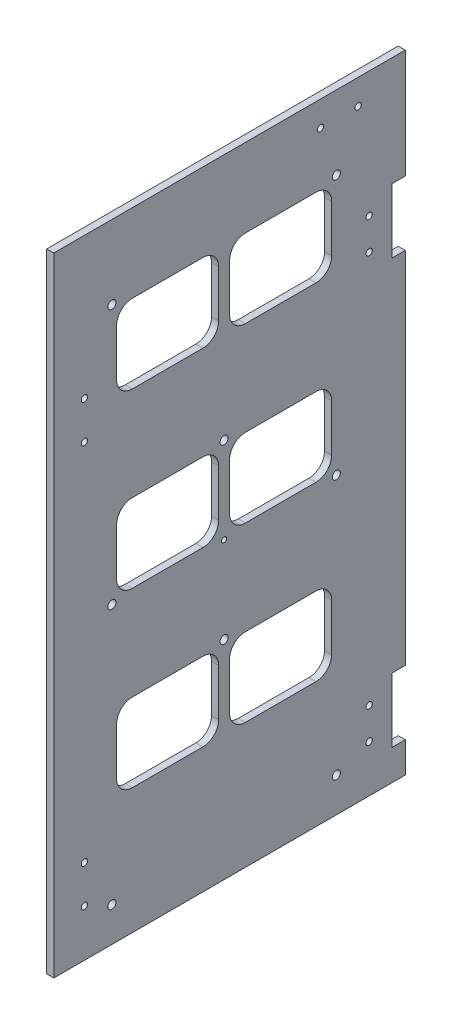
SolidWorks part; units mm, degrees
material "ABS PC"
ref_plane "前视基准面" through (0, 0, 0) normal (0, 0, 1) x (1, 0, 0)
ref_plane "上视基准面" through (0, 0, 0) normal (0, 1, 0) x (1, 0, 0)
ref_plane "右视基准面" through (0, 0, 0) normal (1, 0, 0) x (0, 0, -1)
sketch "草图1" plane through (0, 0, 0) normal (1, 0, 0) x (0, 0, -1)
  line L1 (0, 0) -> (-223.9, 0)
  line L2 (0, 0) -> (0, 400)
  line L3 (0, 400) -> (-223.9, 400)
  line L4 (-223.9, 0) -> (-223.9, 400)
  dimension "D1" = 223.9
  dimension "D2" = 400
extrude "凸台-拉伸1" add sketch "草图1" along normal blind 4.5
sketch "草图2" plane through (4.5, 0, 0) normal (1, 0, 0) x (0, 0, -1)
  line L0 (-204.4, 310) -> (-204.4, 286) construction
  line L1 (-204.4, 54) -> (-204.4, 30) construction
  line L2 (0, 400) -> (-223.9, 400) construction
  line L3 (-223.9, 400) -> (-223.9, 0) construction
  line L4 (-223.9, 0) -> (0, 0) construction
  line L5 (-54, 384) -> (-30, 384) construction
  line L6 (0, 0) -> (0, 400) construction
  line L7 (-23, 0) -> (-23, 306) construction
  line L9 (0, 330.5) -> (-8.5, 330.5)
  line L10 (0, 330.5) -> (0, 289.5)
  line L11 (0, 289.5) -> (-8.5, 289.5)
  line L12 (-8.5, 330.5) -> (-8.5, 289.5)
  line L13 (0, 19.5) -> (-8.5, 19.5)
  line L14 (0, 19.5) -> (0, 60.5)
  line L15 (0, 60.5) -> (-8.5, 60.5)
  line L16 (-8.5, 19.5) -> (-8.5, 60.5)
  circle A0 centre (-204.4, 310) radius 2
  circle A1 centre (-204.4, 286) radius 2
  circle A2 centre (-204.4, 54) radius 2
  circle A3 centre (-204.4, 30) radius 2
  circle A4 centre (-54, 384) radius 2
  circle A5 centre (-30, 384) radius 2
  circle A6 centre (-23, 320) radius 2
  circle A7 centre (-23, 300) radius 2
  circle A8 centre (-23, 50) radius 2
  circle A9 centre (-23, 30) radius 2
  dimension "D1" = 4
  dimension "D9" = 4
  dimension "D10" = 4
  dimension "D2" = 24
  dimension "D3" = 90
  dimension "D4" = 19.5
  dimension "D5" = 24
  dimension "D6" = 30
  dimension "D7" = 24
  dimension "D8" = 30
  dimension "D11" = 16
  dimension "D12" = 20
  dimension "D13" = 20
  dimension "D14" = 23
  dimension "D15" = 30
  dimension "D16" = 300
  dimension "D17" = 41
  dimension "D18" = 41
  dimension "D19" = 8.5
  dimension "D20" = 8.5
  dimension "D21" = 19.5
  dimension "D22" = 289.5
extrude "切除-拉伸1" cut sketch "草图2" against normal blind 10
sketch "草图3" plane through (4.5, 0, 0) normal (1, 0, 0) x (0, 0, -1)
  line L0 (-223.9, 400) -> (-223.9, 0) construction
  line L1 (-173.9, 130) -> (-128.9, 130)
  line L2 (-183.9, 120) -> (-183.9, 90)
  line L3 (-173.9, 80) -> (-128.9, 80)
  line L4 (-118.9, 120) -> (-118.9, 90)
  line L5 (-223.9, 0) -> (0, 0) construction
  line L34 (-101.9, 130) -> (-56.9, 130)
  line L35 (-111.9, 120) -> (-111.9, 90)
  line L36 (-101.9, 80) -> (-56.9, 80)
  line L37 (-46.9, 120) -> (-46.9, 90)
  line L38 (-101.9, 240) -> (-56.9, 240)
  line L39 (-111.9, 230) -> (-111.9, 200)
  line L40 (-101.9, 190) -> (-56.9, 190)
  line L41 (-46.9, 230) -> (-46.9, 200)
  line L42 (-101.9, 350) -> (-56.9, 350)
  line L43 (-111.9, 340) -> (-111.9, 310)
  line L44 (-101.9, 300) -> (-56.9, 300)
  line L45 (-46.9, 340) -> (-46.9, 310)
  line L46 (-173.9, 240) -> (-128.9, 240)
  line L47 (-183.9, 230) -> (-183.9, 200)
  line L48 (-173.9, 190) -> (-128.9, 190)
  line L49 (-118.9, 230) -> (-118.9, 200)
  line L50 (-173.9, 350) -> (-128.9, 350)
  line L51 (-183.9, 340) -> (-183.9, 310)
  line L52 (-173.9, 300) -> (-128.9, 300)
  line L53 (-118.9, 340) -> (-118.9, 310)
  line L54 (-115.4, 353) -> (-115.4, 22) construction
  line L55 (-186.9, 22) -> (-43.9, 22) construction
  line L56 (-186.9, 22) -> (-186.9, 353) construction
  line L57 (-186.9, 353) -> (-43.9, 353) construction
  line L58 (-43.9, 22) -> (-43.9, 353) construction
  arc A4 (-128.9, 80) -> (-118.9, 90) centre (-128.9, 90) ccw
  arc A5 (-183.9, 90) -> (-173.9, 80) centre (-173.9, 90) ccw
  arc A6 (-173.9, 130) -> (-183.9, 120) centre (-173.9, 120) ccw
  arc A7 (-128.9, 130) -> (-118.9, 120) centre (-128.9, 120) cw
  arc A24 (-56.9, 80) -> (-46.9, 90) centre (-56.9, 90) ccw
  arc A25 (-111.9, 90) -> (-101.9, 80) centre (-101.9, 90) ccw
  arc A26 (-101.9, 130) -> (-111.9, 120) centre (-101.9, 120) ccw
  arc A27 (-56.9, 130) -> (-46.9, 120) centre (-56.9, 120) cw
  arc A28 (-56.9, 190) -> (-46.9, 200) centre (-56.9, 200) ccw
  arc A29 (-111.9, 200) -> (-101.9, 190) centre (-101.9, 200) ccw
  arc A30 (-101.9, 240) -> (-111.9, 230) centre (-101.9, 230) ccw
  arc A31 (-56.9, 240) -> (-46.9, 230) centre (-56.9, 230) cw
  arc A32 (-56.9, 300) -> (-46.9, 310) centre (-56.9, 310) ccw
  arc A33 (-111.9, 310) -> (-101.9, 300) centre (-101.9, 310) ccw
  arc A34 (-101.9, 350) -> (-111.9, 340) centre (-101.9, 340) ccw
  arc A35 (-56.9, 350) -> (-46.9, 340) centre (-56.9, 340) cw
  arc A36 (-128.9, 190) -> (-118.9, 200) centre (-128.9, 200) ccw
  arc A37 (-183.9, 200) -> (-173.9, 190) centre (-173.9, 200) ccw
  arc A38 (-173.9, 240) -> (-183.9, 230) centre (-173.9, 230) ccw
  arc A39 (-128.9, 240) -> (-118.9, 230) centre (-128.9, 230) cw
  arc A40 (-128.9, 300) -> (-118.9, 310) centre (-128.9, 310) ccw
  arc A41 (-183.9, 310) -> (-173.9, 300) centre (-173.9, 310) ccw
  arc A42 (-173.9, 350) -> (-183.9, 340) centre (-173.9, 340) ccw
  arc A43 (-128.9, 350) -> (-118.9, 340) centre (-128.9, 340) cw
  circle A44 centre (-43.9, 22) radius 2.6
  circle A45 centre (-186.9, 22) radius 2.6
  circle A46 centre (-43.9, 187.5) radius 2.6
  circle A47 centre (-186.9, 187.5) radius 2.6
  circle A48 centre (-186.9, 353) radius 2.6
  circle A49 centre (-43.9, 353) radius 2.6
  circle A50 centre (-115.4, 187.5) radius 1.6
  circle A51 centre (-115.4, 242.5) radius 2.6
  circle A52 centre (-115.4, 132.5) radius 2.6
  point P40 (-183.9, 80)
  point P43 (-183.9, 130)
  point P46 (-118.9, 130)
  dimension "D7" = 3
  dimension "D5" = 10
  dimension "D12" = 5.2
  dimension "D15" = 3.2
  dimension "D1" = 65
  dimension "D2" = 50
  dimension "D3" = 40
  dimension "D4" = 80
  dimension "D8" = 143
  dimension "D9" = 331
  dimension "D10" = 58
  dimension "D11" = 3
  dimension "D13" = 55
  dimension "D14" = 55
  dimension "D6" = 2
extrude "切除-拉伸2" cut sketch "草图3" against normal up to next
